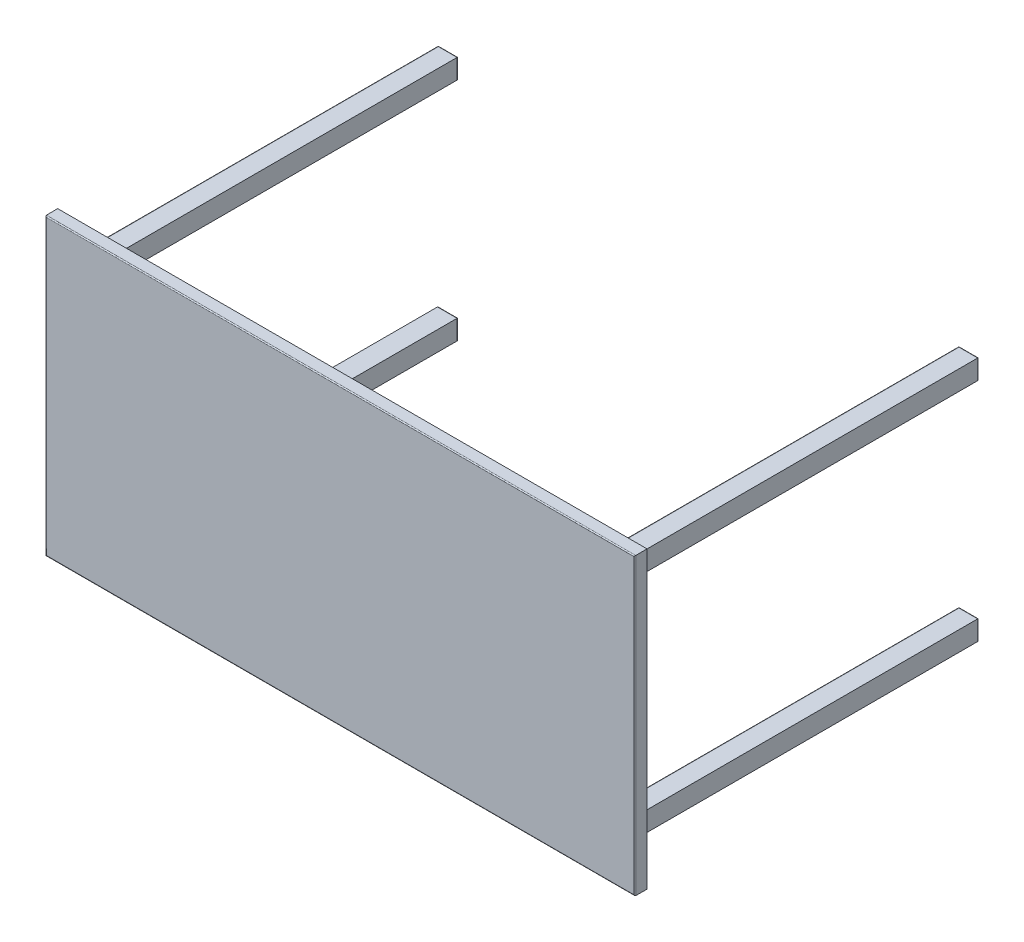
SolidWorks part; units mm, degrees
ref_plane "前视基准面" through (0, 0, 0) normal (0, 0, 1) x (1, 0, 0)
ref_plane "上视基准面" through (0, 0, 0) normal (0, 1, 0) x (1, 0, 0)
ref_plane "右视基准面" through (0, 0, 0) normal (1, 0, 0) x (0, 0, -1)
other "Configuration Table"
sketch "Sketch1" plane through (0, 0, 0) normal (0, 0, 1) x (1, 0, 0)
  line L1 (-600, -300) -> (600, -300)
  line L2 (-600, -300) -> (-600, 300)
  line L3 (-600, 300) -> (600, 300)
  line L4 (600, -300) -> (600, 300)
  line L5 (-600, -300) -> (600, 300) construction
  line L6 (-600, 300) -> (600, -300) construction
  point P0 (0, 0)
extrude "Boss-Extrude1" add sketch "Sketch1" along normal blind 25
ref_plane "Plane1" through (0, 0, 25) normal (0, 0, 1) x (1, 0, 0)
sketch "Sketch2" plane through (0, 0, 25) normal (0, 0, 1) x (1, 0, 0)
  line L1 (-550, -250) -> (-510, -250)
  line L2 (-550, -250) -> (-550, -210)
  line L3 (-550, -210) -> (-510, -210)
  line L4 (-510, -250) -> (-510, -210)
  line L5 (-550, -250) -> (-510, -210) construction
  line L6 (-550, -210) -> (-510, -250) construction
  line L7 (510, -250) -> (550, -250)
  line L8 (510, -250) -> (510, -210)
  line L9 (510, -210) -> (550, -210)
  line L10 (550, -250) -> (550, -210)
  line L11 (510, -250) -> (550, -210) construction
  line L12 (510, -210) -> (550, -250) construction
  line L13 (-550, 210) -> (-510, 210)
  line L14 (-550, 210) -> (-550, 250)
  line L15 (-550, 250) -> (-510, 250)
  line L16 (-510, 210) -> (-510, 250)
  line L17 (-550, 210) -> (-510, 250) construction
  line L18 (-550, 250) -> (-510, 210) construction
  line L19 (510, 210) -> (550, 210)
  line L20 (510, 210) -> (510, 250)
  line L21 (510, 250) -> (550, 250)
  line L22 (550, 210) -> (550, 250)
  line L23 (510, 210) -> (550, 250) construction
  line L24 (510, 250) -> (550, 210) construction
  point P0 (-530, -230)
  point P5 (530, -230)
  point P10 (-530, 230)
  point P15 (530, 230)
extrude "Boss-Extrude2" add sketch "Sketch2" against normal blind 750
fillet "Fillet1" radius 2 20 edges at (510, 250, -362.5) (550, 230, -725) (510, 210, -362.5) (530, 250, -725) (-550, 250, -362.5) (-510, 230, -725) (-550, 210, -362.5) (-530, 250, -725) (510, -210, -362.5) (550, -230, -725) (530, -250, -725) (530, -210, -725) (-550, -230, -725) (-510, -230, -725) (-550, -250, -362.5) (-530, -210, -725) (-600, 0, 25) (600, 0, 25) (0, -300, 25) (0, 300, 25)
